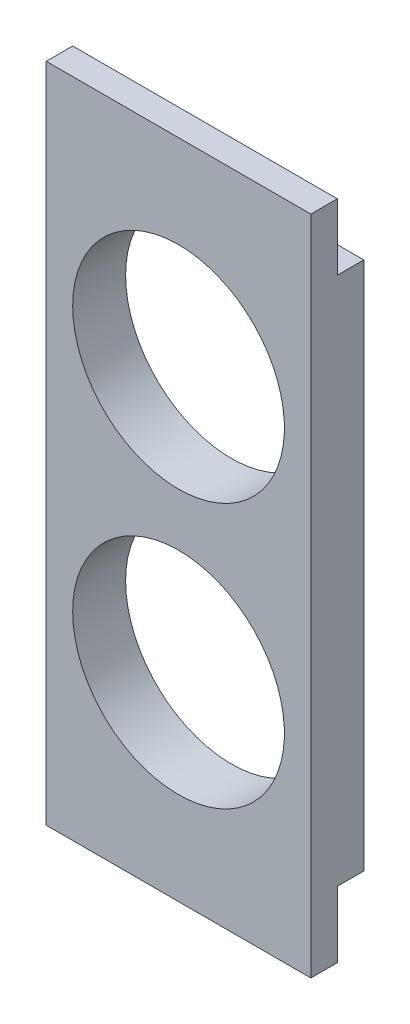
SolidWorks part; units mm, degrees
ref_plane "前视基准面" through (0, 0, 0) normal (0, 0, 1) x (1, 0, 0)
ref_plane "上视基准面" through (0, 0, 0) normal (0, 1, 0) x (1, 0, 0)
ref_plane "右视基准面" through (0, 0, 0) normal (1, 0, 0) x (0, 0, -1)
sketch "草图1" plane through (0, 0, 0) normal (0, 0, 1) x (1, 0, 0)
  line L0 (0, 100) -> (0, -100) construction
  line L1 (50, -100) -> (-50, -100)
  line L2 (50, -100) -> (50, 100)
  line L3 (50, 100) -> (-50, 100)
  line L4 (-50, -100) -> (-50, 100)
  line L5 (50, -100) -> (-50, 100) construction
  line L6 (50, 100) -> (-50, -100) construction
  line L7 (-50, 0) -> (50, 0) construction
  circle A0 centre (0, 50) radius 40
  circle A1 centre (0, -50) radius 40
  point P0 (0, 0)
  dimension "D3" = 80
  dimension "D1" = 100
  dimension "D2" = 200
  dimension "D4" = 50
extrude "凸台-拉伸1" add sketch "草图1" along normal blind 10
sketch "草图2" plane through (0, 0, 10) normal (0, 0, 1) x (1, 0, 0)
  line L0 (-50, 100) -> (-50, -100) construction
  line L1 (50, -125) -> (-50, -125)
  line L2 (50, -125) -> (50, 125)
  line L3 (50, 125) -> (-50, 125)
  line L4 (-50, -125) -> (-50, 125)
  line L5 (50, -125) -> (-50, 125) construction
  line L6 (50, 125) -> (-50, -125) construction
  point P0 (0, 0)
  dimension "D1" = 250
extrude "凸台-拉伸2" add sketch "草图2" along normal blind 10
sketch "草图3" plane through (0, 0, 10) normal (0, 0, -1) x (-1, 0, 0)
  circle A1 centre (0, 50) radius 40
  circle A2 centre (0, 50) radius 40
  circle A3 centre (0, -50) radius 40
  circle A4 centre (0, -50) radius 40
  dimension "D1" = 0
  dimension "D2" = 0
extrude "切除-拉伸1" cut sketch "草图3" against normal through all
